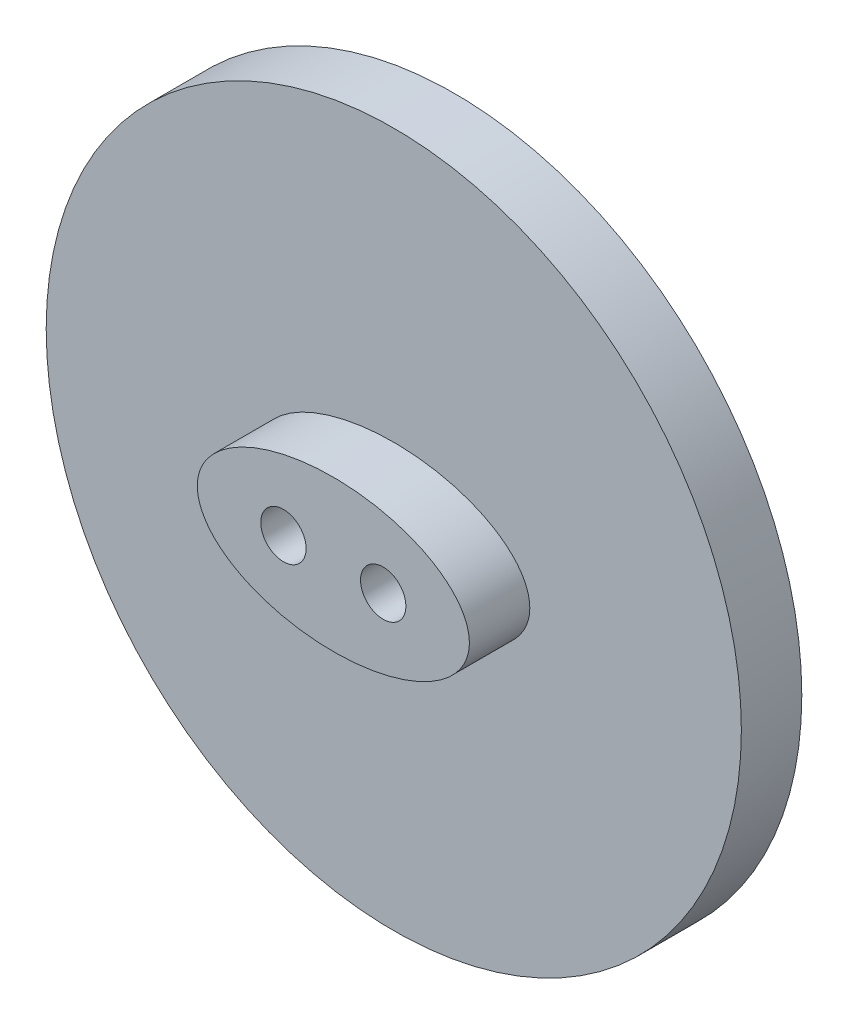
SolidWorks part; units mm, degrees
ref_plane "Plan de face" through (0, 0, 0) normal (0, 0, 1) x (1, 0, 0)
ref_plane "Plan de dessus" through (0, 0, 0) normal (0, 1, 0) x (1, 0, 0)
ref_plane "Plan de droite" through (0, 0, 0) normal (1, 0, 0) x (0, 0, -1)
sketch "Esquisse1" plane through (0, 0, 0) normal (0, 0, 1) x (1, 0, 0)
  circle A1 centre (0, 0) radius 11.5
  dimension "D2" = 23
extrude "Boss.-Extru.1" add sketch "Esquisse1" along normal blind 2 contours A1
sketch "Esquisse6" plane through (0, 0, 2) normal (0, 0, 1) x (1, 0, 0)
  ellipse E0 centre (0, 0) end of major axis (4.5, 0) minor radius 2.5
extrude "Boss.-Extru.5" add sketch "Esquisse6" along normal blind 2
sketch "Esquisse7" plane through (0, 0, 0) normal (0, 0, -1) x (-1, 0, 0)
  line L0 (1.6505, 0) -> (-1.6505, 0) construction
  line L1 (1.6505, -0.75) -> (-1.6505, -0.75) construction
  line L2 (1.6505, 0.75) -> (-1.6505, 0.75) construction
  arc A1 (1.6505, -0.75) -> (1.6505, 0.75) centre (1.6505, 0) ccw construction
  arc A2 (-1.6505, 0.75) -> (-1.6505, -0.75) centre (-1.6505, 0) ccw construction
  circle A3 centre (-0.799, 0.6694) radius 0.0806 construction
  circle A4 centre (1.6505, 0) radius 0.75
  circle A5 centre (-1.6505, 0) radius 0.75
  point P5 (0, 0)
extrude "Enlèv. mat.-Extru.1" cut sketch "Esquisse7" against normal through all
